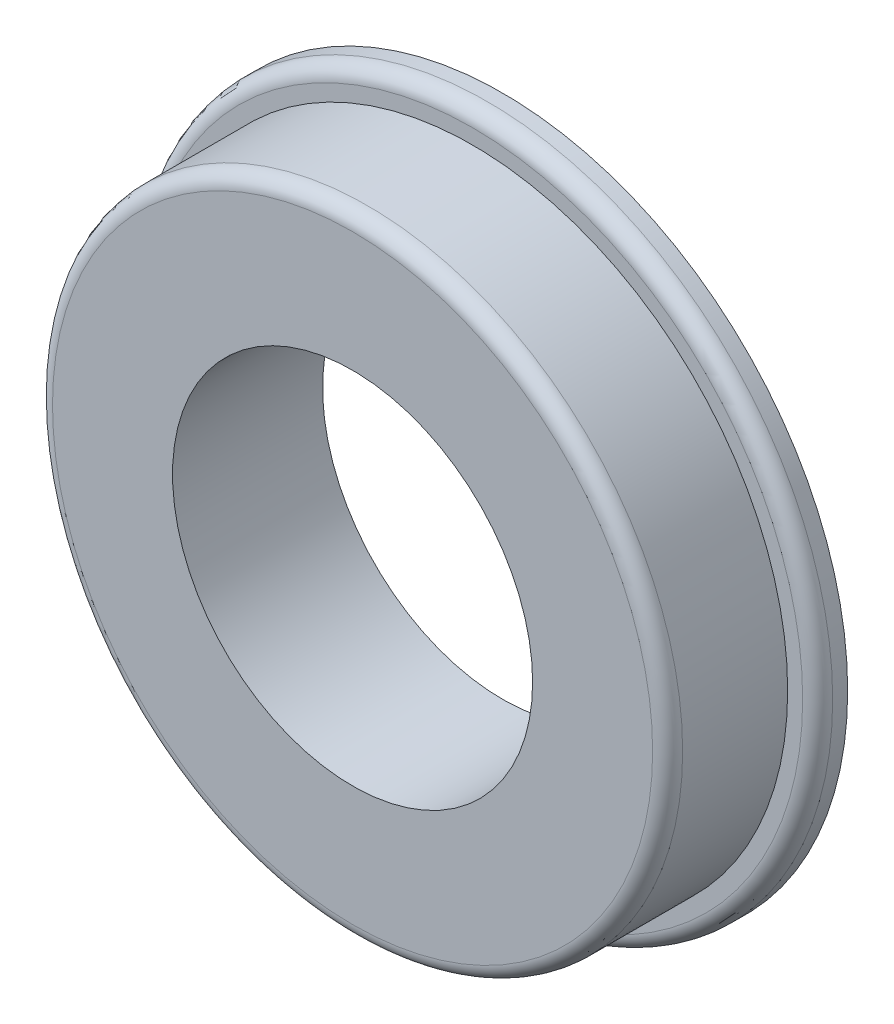
SolidWorks part; units mm, degrees
material "ﾀﾞｸﾀｲﾙ鋳鉄"
ref_plane "正面" through (0, 0, 0) normal (0, 0, 1) x (1, 0, 0)
ref_plane "平面" through (0, 0, 0) normal (0, 1, 0) x (1, 0, 0)
ref_plane "右側面" through (0, 0, 0) normal (1, 0, 0) x (0, 0, -1)
sketch "ｽｹｯﾁ1" plane through (0, 0, 0) normal (0, 0, 1) x (1, 0, 0)
  circle A0 centre (0, 0) radius 11.5
  dimension "D1" = 23
extrude "ﾎﾞｽ - 押し出し1" add sketch "ｽｹｯﾁ1" along normal blind 1
sketch "ｽｹｯﾁ2" plane through (0, 0, 1) normal (0, 0, 1) x (1, 0, 0)
  circle A0 centre (0, 0) radius 10.5
  dimension "D1" = 21
extrude "ﾎﾞｽ - 押し出し2" add sketch "ｽｹｯﾁ2" along normal blind 4
sketch "ｽｹｯﾁ3" plane through (0, 0, 5) normal (0, 0, 1) x (1, 0, 0)
  circle A0 centre (0, 0) radius 6
  dimension "D1" = 12
extrude "ｶｯﾄ - 押し出し1" cut sketch "ｽｹｯﾁ3" against normal blind 9
fillet "ﾌｨﾚｯﾄ1" radius 0.5 2 edges at (11.5, 0, 1) (10.5, 0, 5)
